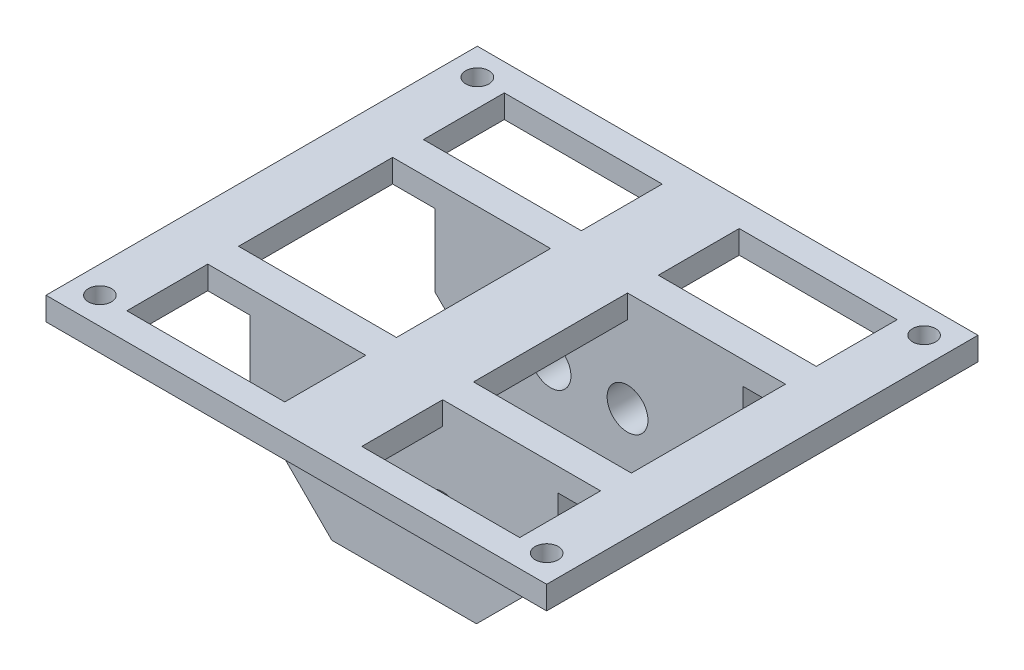
SolidWorks part; units mm, degrees
ref_plane "Front Plane" through (0, 0, 0) normal (0, 0, 1) x (1, 0, 0)
ref_plane "Top Plane" through (0, 0, 0) normal (0, 1, 0) x (1, 0, 0)
ref_plane "Right Plane" through (0, 0, 0) normal (1, 0, 0) x (0, 0, -1)
sketch "Sketch1" plane through (0, 0, 0) normal (0, 1, 0) x (1, 0, 0)
  line L0 (3.5, 52.5) -> (61.5, 52.5) construction
  line L1 (0, 0) -> (65, 0)
  line L2 (0, 0) -> (0, 56)
  line L3 (0, 56) -> (65, 56)
  line L4 (65, 0) -> (65, 56)
  line L5 (61.5, 52.5) -> (61.5, 3.5) construction
  line L6 (61.5, 3.5) -> (3.5, 3.5) construction
  line L7 (3.5, 3.5) -> (3.5, 52.5) construction
  line L14 (0, 28) -> (65, 28) construction
  line L17 (7, 38) -> (27.5, 38)
  line L18 (27.5, 38) -> (27.5, 18)
  line L19 (27.5, 18) -> (7, 18)
  line L20 (37.5, 38) -> (37.5, 18)
  line L21 (32.5, 56) -> (32.5, 0) construction
  line L22 (7, 38) -> (7, 18)
  line L23 (58, 18) -> (58, 38)
  line L24 (37.5, 38) -> (58, 38)
  line L25 (37.5, 18) -> (58, 18)
  line L27 (7, 52.5) -> (27.5, 52.5)
  line L28 (7, 52.5) -> (7, 42)
  line L29 (7, 42) -> (27.5, 42)
  line L30 (58, 52.5) -> (58, 42)
  line L34 (27.5, 42) -> (27.5, 52.5)
  line L35 (37.5, 42) -> (37.5, 52.5)
  line L36 (37.5, 42) -> (58, 42)
  line L37 (37.5, 52.5) -> (58, 52.5)
  line L38 (37.5, 3.5) -> (58, 3.5)
  line L39 (37.5, 14) -> (37.5, 3.5)
  line L40 (37.5, 14) -> (58, 14)
  line L41 (58, 3.5) -> (58, 14)
  line L42 (7, 3.5) -> (7, 14)
  line L43 (7, 14) -> (27.5, 14)
  line L44 (27.5, 14) -> (27.5, 3.5)
  line L45 (7, 3.5) -> (27.5, 3.5)
  circle A0 centre (3.5, 52.5) radius 3.5 construction
  circle A1 centre (61.5, 52.5) radius 3.5 construction
  circle A2 centre (61.5, 3.5) radius 3.5 construction
  circle A3 centre (3.5, 3.5) radius 3.5 construction
  circle A4 centre (3.5, 52.5) radius 1.5
  circle A5 centre (61.5, 52.5) radius 1.5
  circle A6 centre (61.5, 3.5) radius 1.5
  circle A7 centre (3.5, 3.5) radius 1.5
  point P18 (6, 6)
  point P19 (6, 50)
  point P20 (59, 50)
  point P21 (59, 6)
  dimension "D4" = 7
  dimension "D5" = 3
  dimension "D1" = 56
  dimension "D2" = 65
  dimension "D3" = 58
  dimension "D7" = 3.5
  dimension "D8" = 10
  dimension "D6" = 3.5
  dimension "D9" = 20
  dimension "D10" = 4
extrude "Boss-Extrude1" add sketch "Sketch1" along normal blind 3
sketch "Sketch5" plane through (0, 0, 0) normal (0, -1, 0) x (1, 0, 0)
  line L0 (7, -18) -> (27.5, -18) construction
  line L1 (12.5, -18) -> (52.5, -18)
  line L2 (12.5, -18) -> (12.5, -14)
  line L3 (12.5, -14) -> (52.5, -14)
  line L4 (52.5, -18) -> (52.5, -14)
  line L5 (27.5, -38) -> (7, -38) construction
  line L6 (12.5, -38) -> (52.5, -38)
  line L7 (12.5, -38) -> (12.5, -42)
  line L8 (12.5, -42) -> (52.5, -42)
  line L9 (52.5, -38) -> (52.5, -42)
  line L10 (32.5, 0) -> (32.5, -56) construction
  line L11 (0, 0) -> (65, 0) construction
  line L12 (65, -56) -> (0, -56) construction
  dimension "D1" = 4
  dimension "D2" = 4
  dimension "D3" = 40
extrude "Boss-Extrude4" add sketch "Sketch5" along normal blind 20
sketch "Sketch6" plane through (0, 0, -14) normal (0, 0, 1) x (1, 0, 0)
  line L0 (27.5, -10) -> (37.5, -10) construction
  line L1 (12.5, -10) -> (52.5, -10) construction
  line L2 (12.5, -20) -> (12.5, 0) construction
  line L3 (52.5, -20) -> (52.5, 0) construction
  line L4 (32.5, 0) -> (32.5, -20) construction
  line L5 (0, 0) -> (65, 0) construction
  line L6 (52.5, -20) -> (12.5, -20) construction
  line L21 (12.5, -9.3934) -> (12.5, -20)
  line L22 (12.5, -20) -> (23.1066, -20)
  line L23 (23.1066, -20) -> (12.5, -9.3934)
  line L24 (41.8934, -20) -> (52.5, -20)
  line L25 (52.5, -20) -> (52.5, -9.3934)
  line L26 (52.5, -9.3934) -> (41.8934, -20)
  circle A0 centre (27.5, -10) radius 2.65
  circle A1 centre (37.5, -10) radius 2.65
  dimension "D1" = 5.3
  dimension "D2" = 10
  dimension "D4" = 15
  dimension "D3" = 45
extrude "Cut-Extrude1" cut sketch "Sketch6" against normal up to surface (28 mm away) up to face at (32.5, -2.3333, -42)
